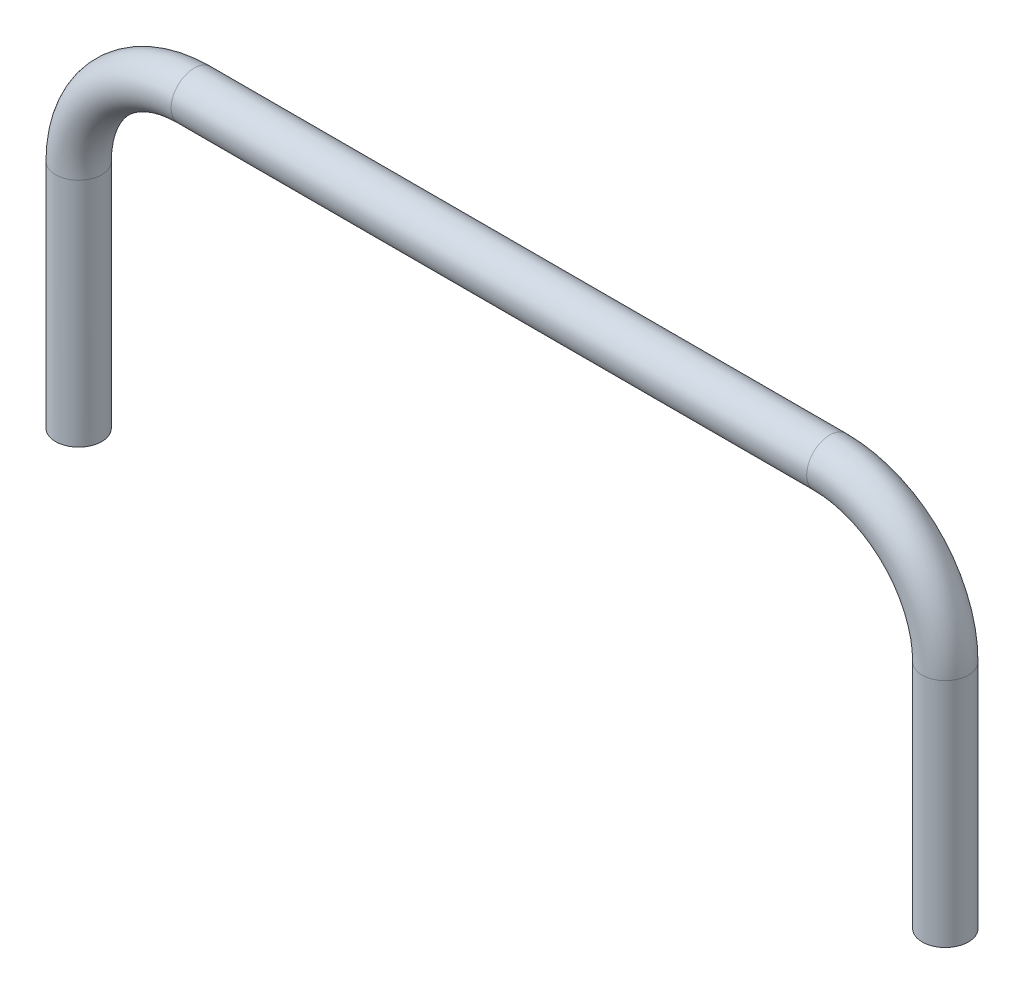
SolidWorks part; units mm, degrees
ref_plane "Front Plane" through (0, 0, 0) normal (0, 0, 1) x (1, 0, 0)
ref_plane "Top Plane" through (0, 0, 0) normal (0, 1, 0) x (1, 0, 0)
ref_plane "Right Plane" through (0, 0, 0) normal (1, 0, 0) x (0, 0, -1)
sketch "Sketch1" plane through (0, 0, 0) normal (0, 0, 1) x (1, 0, 0)
  line L0 (-75, 0) -> (-75, 40)
  line L1 (-55, 60) -> (55, 60)
  line L2 (75, 40) -> (75, 0)
  arc A0 (55, 60) -> (75, 40) centre (55, 40) cw
  arc A1 (-75, 40) -> (-55, 60) centre (-55, 40) cw
  point P5 (0, 60)
  point P8 (75, 60)
  point P11 (-75, 60)
  dimension "D1" = 150
  dimension "D3" = 20
  dimension "D2" = 60
sweep "Sweep1" add path "Sketch1" circular profile diameter 8 parameters "D3"=8
